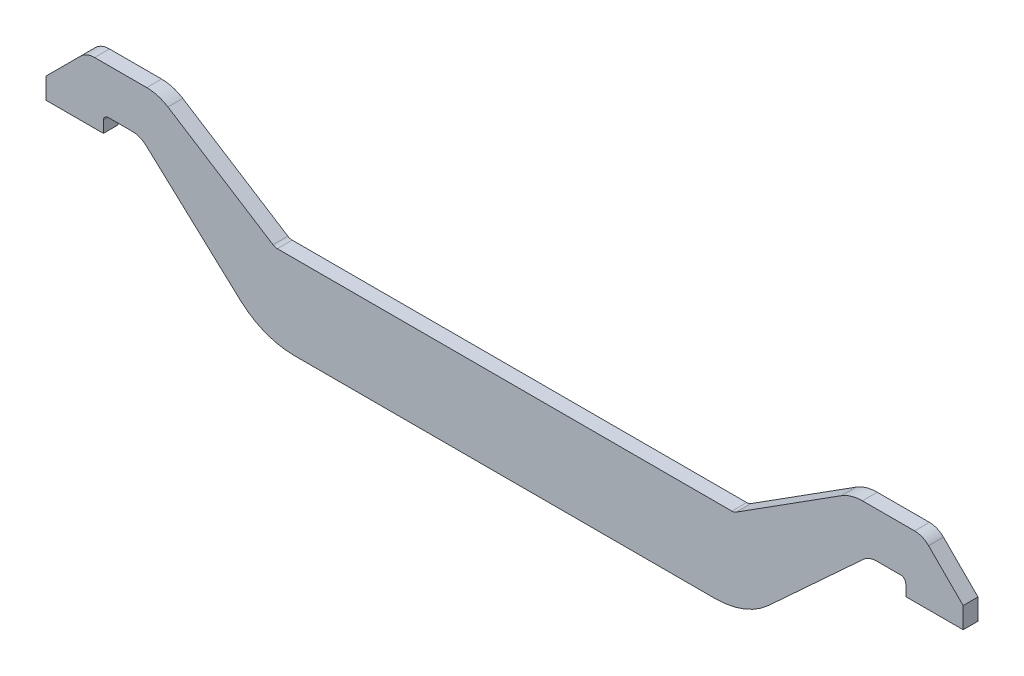
SolidWorks part; units mm, degrees
material "Alloy Steel"
ref_plane "Front Plane" through (0, 0, 0) normal (0, 0, 1) x (1, 0, 0)
ref_plane "Top Plane" through (0, 0, 0) normal (0, 1, 0) x (1, 0, 0)
ref_plane "Right Plane" through (0, 0, 0) normal (1, 0, 0) x (0, 0, -1)
sketch "Sketch1" plane through (0, 0, 0) normal (0, 0, 1) x (1, 0, 0)
  line L0 (-25.4657, 26.9875) -> (77.47, 26.9875) construction
  line L1 (-15.176, 0) -> (77.47, 0) construction
  line L2 (154.94, 0) -> (194.3735, 36.322)
  line L3 (-1086.8586, 36.322) -> (-69.6595, 36.322) construction
  line L4 (77.47, 0) -> (77.47, 100.6433) construction
  line L5 (0, 0) -> (154.94, 0)
  line L6 (206.1845, 36.322) -> (194.3735, 36.322)
  line L7 (3.81, 26.9875) -> (151.13, 26.9875)
  line L8 (206.1845, 31.115) -> (206.1845, 36.322)
  line L9 (-56.7055, 50.8) -> (-33.655, 50.8)
  line L10 (-69.6595, 37.846) -> (-69.6595, 36.322)
  line L11 (-51.2445, 36.322) -> (-39.4335, 36.322)
  line L12 (224.5995, 31.115) -> (206.1845, 31.115)
  line L13 (0, 0) -> (-39.4335, 36.322)
  line L14 (3.81, 26.9875) -> (-33.655, 50.8)
  line L15 (224.5995, 37.846) -> (224.5995, 31.115)
  line L16 (224.5995, 37.846) -> (211.6455, 50.8)
  line L17 (-69.6595, 37.846) -> (-56.7055, 50.8)
  line L18 (-69.6595, 37.846) -> (-69.6595, 31.115)
  line L19 (-51.2445, 31.115) -> (-51.2445, 36.322)
  line L20 (-69.6595, 31.115) -> (-51.2445, 31.115)
  line L21 (-56.7055, 50.8) -> (-33.655, 50.8) construction
  line L22 (-51.2445, 36.322) -> (-39.4335, 36.322) construction
  line L23 (211.6455, 50.8) -> (188.595, 50.8)
  line L24 (151.13, 26.9875) -> (188.595, 50.8)
  line L25 (-60.452, 31.115) -> (-60.452, 78.4909) construction
  dimension "D1" = 26.9875
  dimension "D2" = 36.322
  dimension "D3" = 50.8
  dimension "D4" = 137.922
  dimension "D5" = 77.47
  dimension "D6" = 30.226
  dimension "D7" = 31.115
  dimension "D8" = 73.66
  dimension "D9" = 135
  dimension "D10" = 111.125
  dimension "D11" = 6.731
  dimension "D12" = 18.415
extrude "Boss-Extrude1" add sketch "Sketch1" along normal blind 4.7625
fillet "1.0 Radius" radius 25.4 2 edges at (0, 0, 2.3813) (154.94, 0, 2.3813)
fillet "0.1 Radius" radius 2.54 2 edges at (3.81, 26.9875, 2.3813) (151.13, 26.9875, 2.3813)
fillet "0.25 Radius" radius 6.35 4 edges at (194.3735, 36.322, 2.3813) (-39.4335, 36.322, 2.3813) (-56.7055, 50.8, 2.3813) (211.6455, 50.8, 2.3813)
fillet "0.5 Radius" radius 12.7 2 edges at (-33.655, 50.8, 2.3813) (188.595, 50.8, 2.3813)
fillet "0.0625 Radius" radius 1.5875 2 edges at (206.1845, 36.322, 2.3813) (-51.2445, 36.322, 2.3813)
